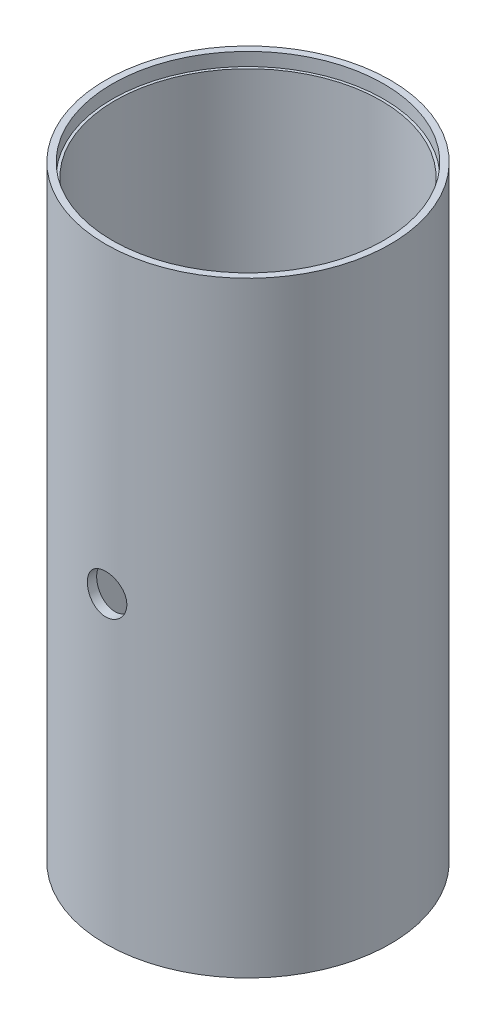
SolidWorks part; units mm, degrees
material "Жесткий ПВХ"
ref_plane "Спереди" through (0, 0, 0) normal (0, 0, 1) x (1, 0, 0)
ref_plane "Сверху" through (0, 0, 0) normal (0, 1, 0) x (1, 0, 0)
ref_plane "Справа" through (0, 0, 0) normal (1, 0, 0) x (0, 0, -1)
sketch "Эскиз1" plane through (0, 0, 0) normal (0, 1, 0) x (1, 0, 0)
  circle A0 centre (0, 0) radius 54
  circle A1 centre (0, 0) radius 50.5
  dimension "D1" = 108
  dimension "D2" = 101
extrude "Бобышка-Вытянуть1" add sketch "Эскиз1" along normal blind 230
sketch "Эскиз2" plane through (0, 230, 0) normal (0, 1, 0) x (1, 0, 0)
  circle A0 centre (0, 0) radius 51.5
  dimension "D1" = 103
extrude "Вырез-Вытянуть1" cut sketch "Эскиз2" against normal blind 5
sketch "Эскиз3" plane through (0, 0, 0) normal (0, 0, 1) x (1, 0, 0)
  line L0 (0, 230) -> (0, 0) construction
  line L1 (51.5, 230) -> (-51.5, 230) construction
  line L2 (-54, 0) -> (54, 0) construction
  circle A0 centre (0, 115) radius 7.5
  dimension "D1" = 15
  dimension "D2" = 115
extrude "Вырез-Вытянуть2" cut sketch "Эскиз3" along normal blind 101
